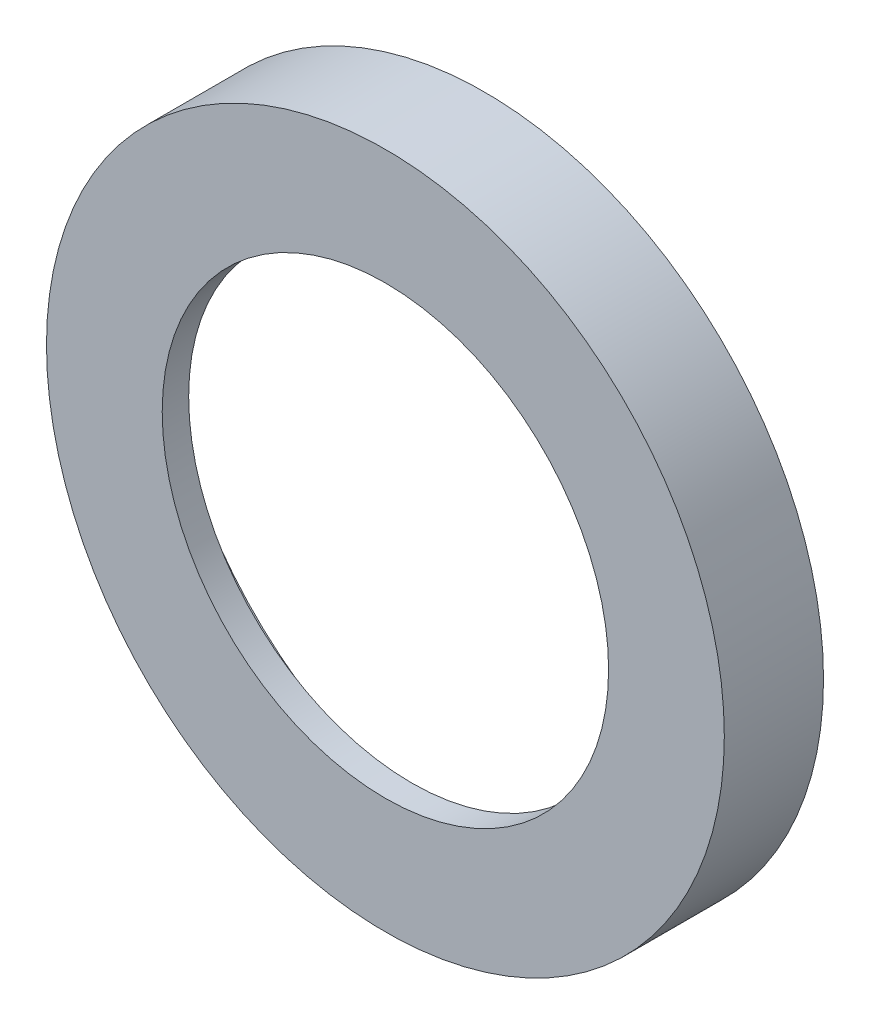
SolidWorks part; units mm, degrees
ref_plane "Plano frontal" through (0, 0, 0) normal (0, 0, 1) x (1, 0, 0)
ref_plane "Plano superior" through (0, 0, 0) normal (0, 1, 0) x (1, 0, 0)
ref_plane "Plano direito" through (0, 0, 0) normal (1, 0, 0) x (0, 0, -1)
sketch "Esboço1" plane through (0, 0, 0) normal (0, 0, 1) x (1, 0, 0)
  circle A0 centre (0, 0) radius 10.25
  dimension "D1" = 20.5
extrude "Ressalto-extrusão1" add sketch "Esboço1" along normal blind 3
sketch "Esboço2" plane through (0, 0, 0) normal (0, 0, -1) x (-1, 0, 0)
  circle A0 centre (0, 0) radius 9.8
  dimension "D1" = 19.6
extrude "Corte-extrusão1" cut sketch "Esboço2" against normal blind 2.2
sketch "Esboço3" plane through (0, 0, 2.2) normal (0, 0, -1) x (-1, 0, 0)
  circle A0 centre (0, 0) radius 6.75
  dimension "D1" = 13.5
extrude "Corte-extrusão2" cut sketch "Esboço3" against normal through all
